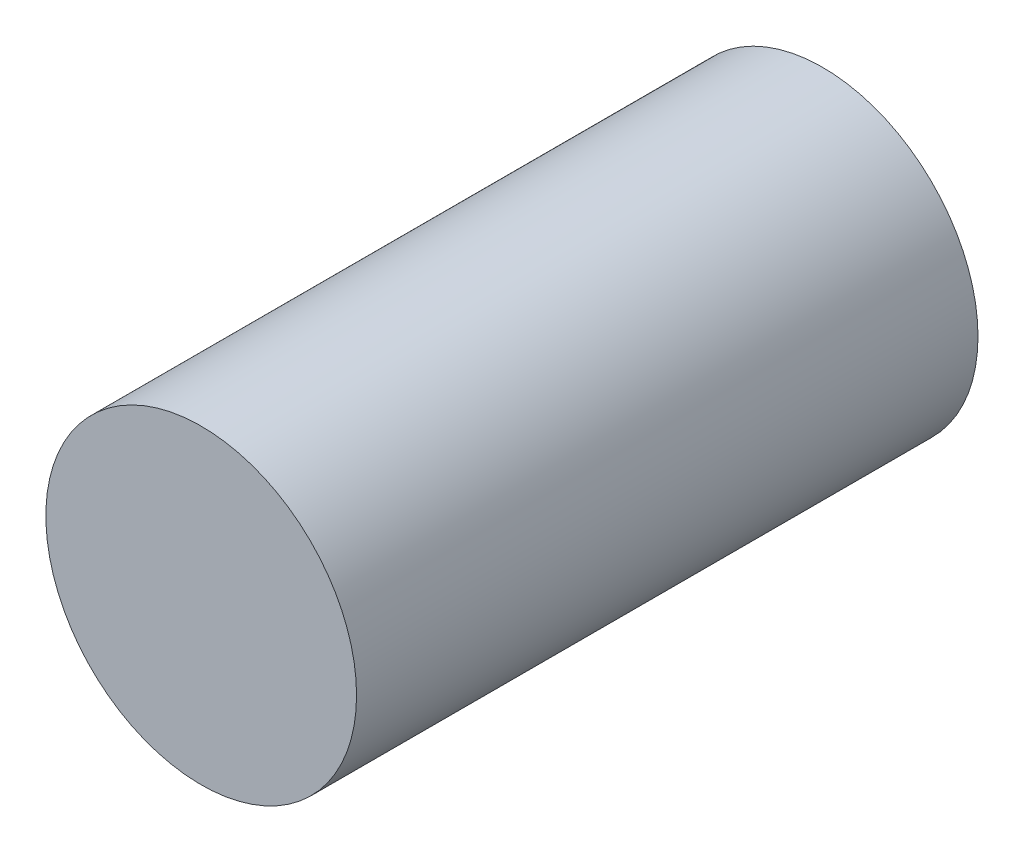
SolidWorks part; units mm, degrees
ref_plane "Front Plane" through (0, 0, 0) normal (0, 0, 1) x (1, 0, 0)
ref_plane "Top Plane" through (0, 0, 0) normal (0, 1, 0) x (1, 0, 0)
ref_plane "Right Plane" through (0, 0, 0) normal (1, 0, 0) x (0, 0, -1)
other "Configuration Table"
sketch "Sketch1" plane through (0, 0, 0) normal (0, 0, 1) x (1, 0, 0)
  circle A0 centre (200, 105) radius 50
extrude "TOPPING_sog_kompresor_yatik_D100" add sketch "Sketch1" against normal blind 200 from offset 400 separate body
